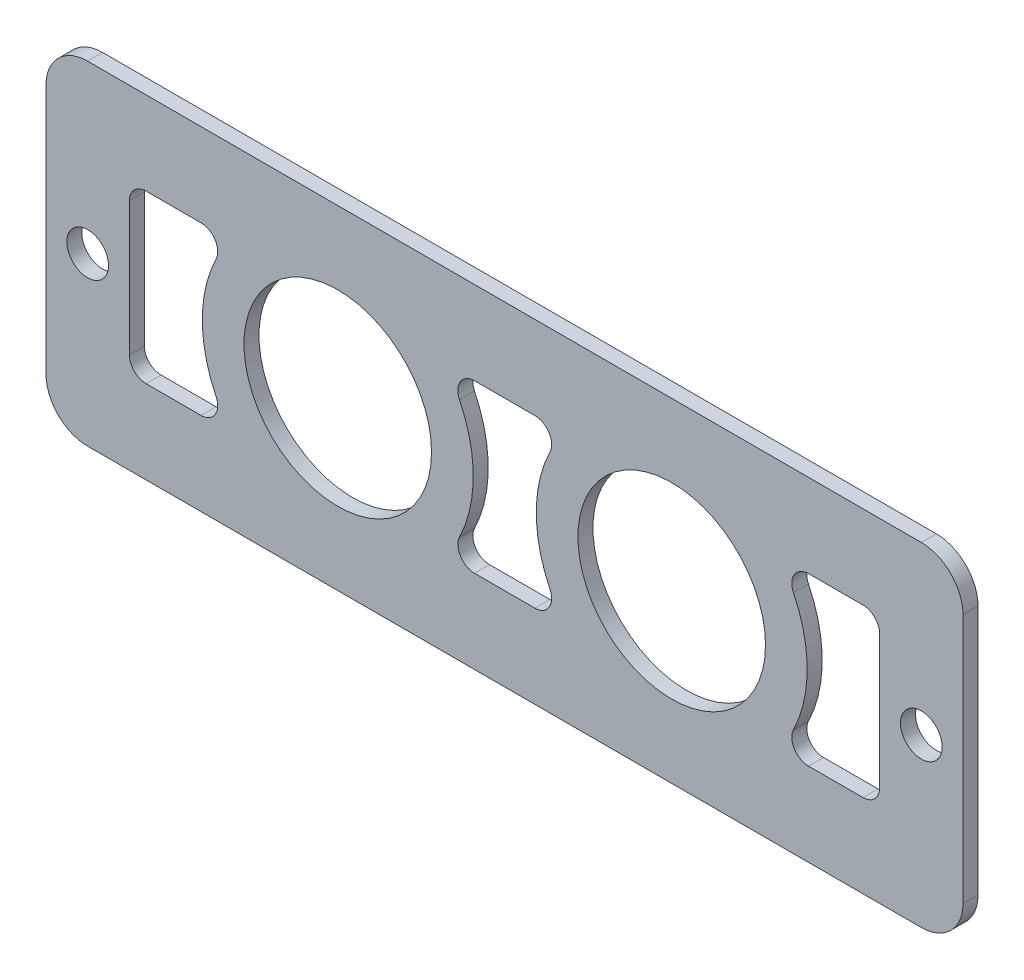
SolidWorks part; units mm, degrees
ref_plane "Front Plane" through (0, 0, 0) normal (0, 0, 1) x (1, 0, 0)
ref_plane "Top Plane" through (0, 0, 0) normal (0, 1, 0) x (1, 0, 0)
ref_plane "Right Plane" through (0, 0, 0) normal (1, 0, 0) x (0, 0, -1)
sketch "Sketch1" plane through (0, 0, 0) normal (0, 0, 1) x (1, 0, 0)
  line L0 (-63.5, 0) -> (63.5, 0) construction
  line L1 (-69.85, 25.4) -> (69.85, 25.4)
  line L2 (-69.85, 25.4) -> (-69.85, -25.4)
  line L3 (-69.85, -25.4) -> (69.85, -25.4)
  line L4 (69.85, 25.4) -> (69.85, -25.4)
  line L5 (-69.85, 25.4) -> (69.85, -25.4) construction
  line L6 (-69.85, -25.4) -> (69.85, 25.4) construction
  circle A0 centre (-63.5, 0) radius 3.175
  circle A1 centre (63.5, 0) radius 3.175
  circle A2 centre (-25.4, 0) radius 26.67 construction
  circle A3 centre (25.4762, 0) radius 26.67 construction
  circle A4 centre (-25.4, 0) radius 14.2875
  circle A5 centre (25.4762, 0) radius 14.2875
  point P0 (0, 0)
  dimension "D1" = 6.35
  dimension "D4" = 50.8762
  dimension "D7" = 28.575
  dimension "D2" = 127
  dimension "D3" = 38.1
  dimension "D5" = 139.7
  dimension "D6" = 50.8
extrude "Boss-Extrude1" add sketch "Sketch1" along normal mid plane 2.286
fillet "Fillet1" radius 6.35 4 edges at (69.85, -25.4, 0) (-69.85, -25.4, 0) (-69.85, 25.4, 0) (69.85, 25.4, 0)
sketch "Sketch2" plane through (0, 0, 1.143) normal (0, 0, 1) x (1, 0, 0)
  line L8 (-57.15, -12.7) -> (57.15, -12.7)
  line L9 (57.15, -12.7) -> (57.15, 12.7)
  line L10 (57.15, 12.7) -> (-57.15, 12.7)
  line L11 (-57.15, 12.7) -> (-57.15, -12.7)
  line L12 (-57.15, -12.7) -> (57.15, -12.7)
  line L13 (57.15, -12.7) -> (57.15, 12.7)
  line L14 (57.15, 12.7) -> (-57.15, 12.7)
  line L15 (-57.15, 12.7) -> (-57.15, -12.7)
  circle A9 centre (-25.4, 0) radius 20.6375
  circle A10 centre (-25.4, 0) radius 20.6375
  circle A12 centre (25.4762, 0) radius 20.6375
  circle A13 centre (25.4762, 0) radius 20.6375
  dimension "D1" = 12.7
  dimension "D2" = 6.35
  dimension "D3" = 6.35
extrude "Cut-Extrude1" cut sketch "Sketch2" against normal blind 2.54 contours A10 L14 L15 L12 | A13 L14 A10 L12 | A13 L12 L13 L14
fillet "Fillet2" radius 2.54 12 edges at (9.2092, 12.7, 0) (41.7432, 12.7, 0) (57.15, 12.7, 0) (57.15, -12.7, 0) (-41.667, -12.7, 0) (-9.133, -12.7, 0) (-57.15, -12.7, 0) (-57.15, 12.7, 0) (-41.667, 12.7, 0) (-9.133, 12.7, 0) (9.2092, -12.7, 0) (41.7432, -12.7, 0)
